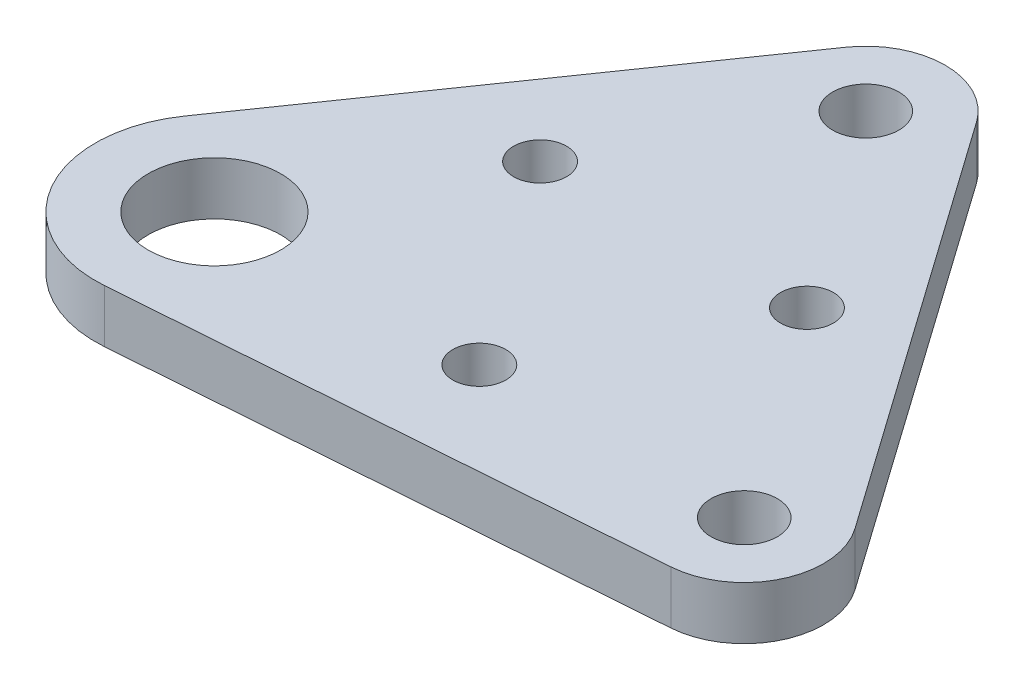
SolidWorks part; units mm, degrees
material "6061-T6 (SS)"
ref_plane "Front Plane" through (0, 0, 0) normal (0, 0, 1) x (1, 0, 0)
ref_plane "Top Plane" through (0, 0, 0) normal (0, 1, 0) x (1, 0, 0)
ref_plane "Right Plane" through (0, 0, 0) normal (1, 0, 0) x (0, 0, -1)
sketch "Sketch1" plane through (0, 0, 0) normal (0, 1, 0) x (1, 0, 0)
  line L0 (28.575, 49.4934) -> (0, 0) construction
  line L1 (0, 0) -> (63.5, 0) construction
  line L2 (1.0716, -14.2473) -> (64.2144, -9.4982)
  line L3 (-11.735, 8.15) -> (20.7517, 54.9267)
  line L4 (36.3575, 54.9851) -> (71.2825, 5.4917)
  line L5 (0, 0) -> (53.82, 30.2384) construction
  circle A0 centre (28.575, 49.4934) radius 3.9687
  circle A1 centre (0, 0) radius 7.9375
  circle A2 centre (63.5, 0) radius 3.9688
  arc A3 (-11.735, 8.15) -> (1.0716, -14.2473) centre (0, 0) ccw
  arc A4 (36.3575, 54.9851) -> (20.7517, 54.9267) centre (28.575, 49.4934) ccw
  arc A5 (64.2144, -9.4982) -> (71.2825, 5.4917) centre (63.5, 0) ccw
  circle A6 centre (14.2875, 24.7467) radius 3.175
  circle A7 centre (31.75, 0) radius 3.175
  circle A8 centre (45.472, 25.5481) radius 3.175
  point P1 (63.5, 0)
  point P2 (28.575, 49.4934)
  dimension "D4" = 7.9375
  dimension "D5" = 15.875
  dimension "D6" = 28.575
  dimension "D7" = 19.05
  dimension "D8" = 6.35
  dimension "D1" = 57.15
  dimension "D2" = 63.5
  dimension "D3" = 60
  dimension "D9" = 9.525
extrude "Boss-Extrude1" add sketch "Sketch1" along normal blind 6.35
